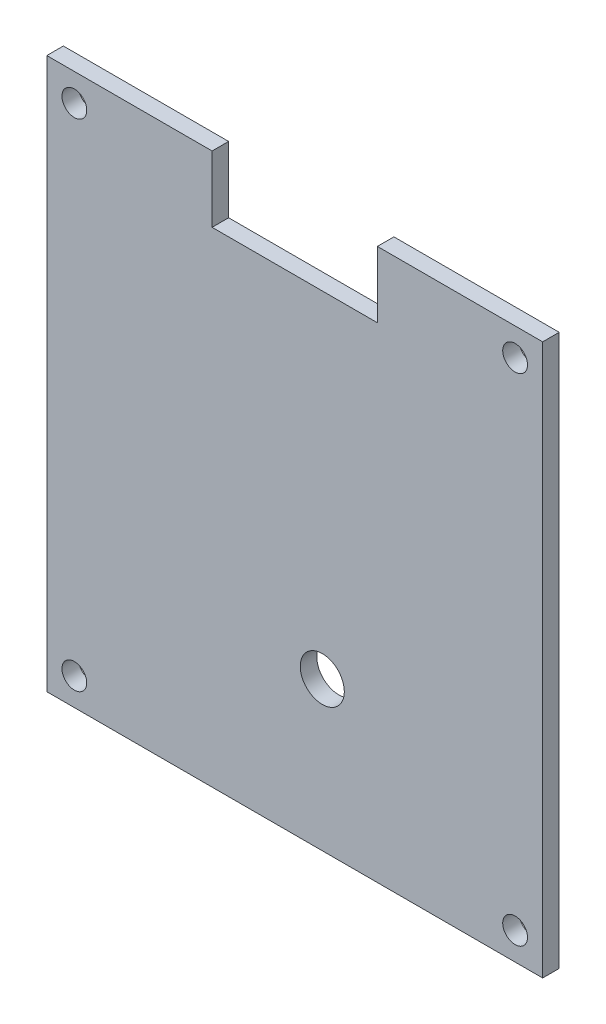
SolidWorks part; units mm, degrees
ref_plane "Front Plane" through (0, 0, 0) normal (0, 0, 1) x (1, 0, 0)
ref_plane "Top Plane" through (0, 0, 0) normal (0, 1, 0) x (1, 0, 0)
ref_plane "Right Plane" through (0, 0, 0) normal (1, 0, 0) x (0, 0, -1)
ref_plane "Plane1" through (0, 0, 0) normal (0, 0, -1) x (-1, 0, 0)
sketch "Sketch1" plane through (0, 0, 0) normal (0, 0, -1) x (-1, 0, 0)
  line L0 (15, 50) -> (15, 38)
  line L1 (15, 38) -> (-15, 38)
  line L2 (-15, 38) -> (-15, 50)
  line L3 (-15, 50) -> (-45, 50)
  line L4 (-45, 50) -> (-45, -50)
  line L5 (-45, -50) -> (45, -50)
  line L6 (45, -50) -> (45, 50)
  line L7 (45, 50) -> (15, 50)
  circle A0 centre (-5, -23) radius 4
  circle A1 centre (40, 45) radius 2.25
  circle A2 centre (-40, 45) radius 2.25
  circle A3 centre (-40, -45) radius 2.25
  circle A4 centre (40, -45) radius 2.25
extrude "Boss-Extrude1" add sketch "Sketch1" against normal blind 3
